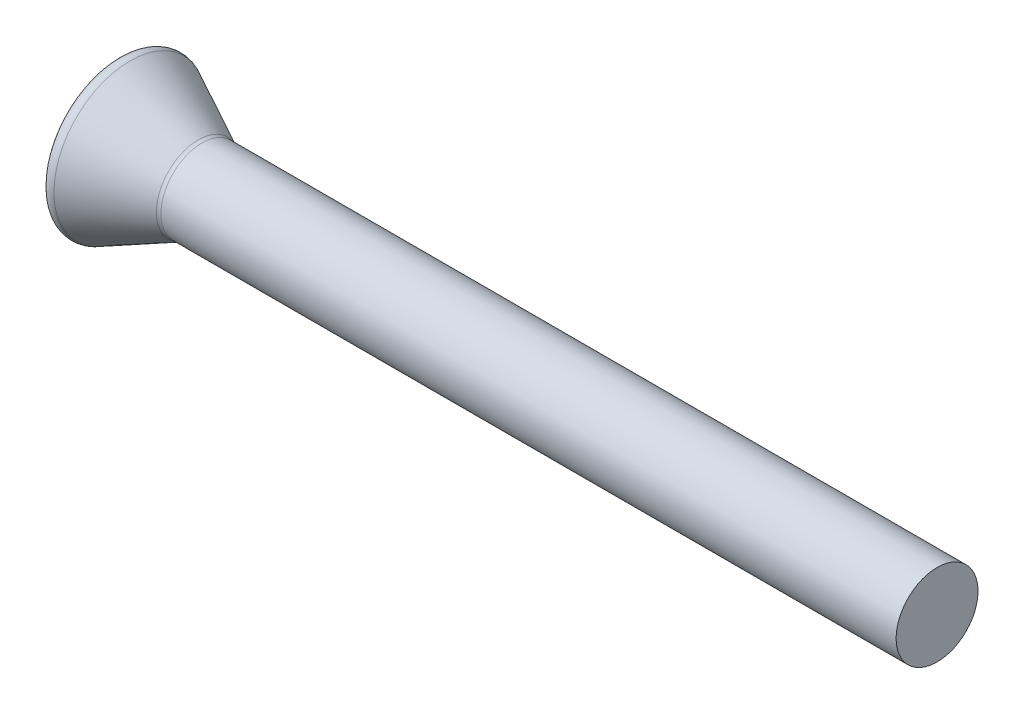
SolidWorks part; units mm, degrees
ref_plane "前视基准面" through (0, 0, 0) normal (0, 0, 1) x (1, 0, 0)
ref_plane "上视基准面" through (0, 0, 0) normal (0, 1, 0) x (1, 0, 0)
ref_plane "右视基准面" through (0, 0, 0) normal (1, 0, 0) x (0, 0, -1)
sketch "草图1" plane through (0, 0, 0) normal (0, 0, 1) x (1, 0, 0)
  line L0 (0, 0) -> (0, 1)
  line L1 (0, 1) -> (1, 0.5)
  line L2 (1, 0.5) -> (10, 0.5)
  line L3 (10, 0.5) -> (10, 0)
  line L4 (10, 0) -> (0, 0)
  dimension "D1" = 1
  dimension "D2" = 0.5
  dimension "D3" = 10
  dimension "D4" = 1
revolve "旋转1" add sketch "草图1" angle 360 about L4
cosmetic thread "装饰螺纹线1" parameters "D2"=0.9
fillet "圆角1" radius 0.1 2 edges at (1, 0.5, 0) (0, 1, 0)
